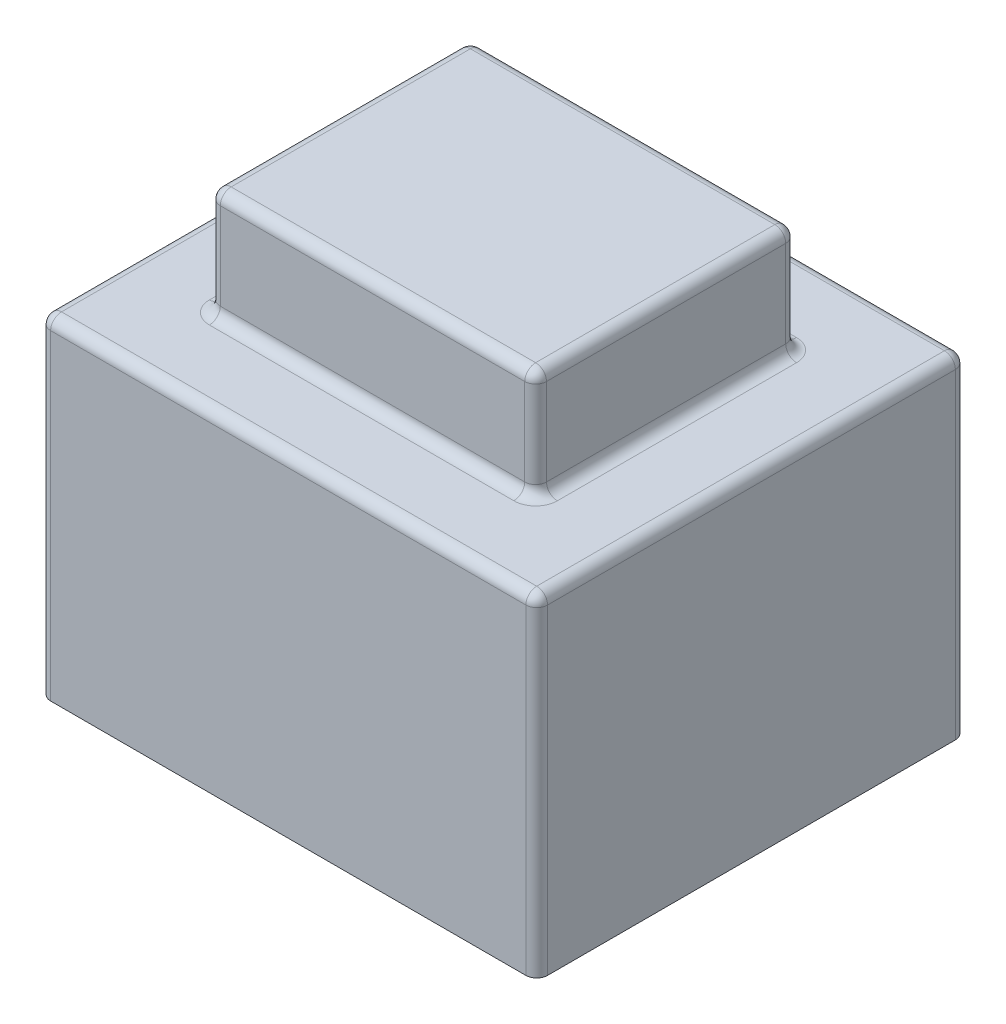
SolidWorks part; units mm, degrees
ref_plane "Спереди" through (0, 0, 0) normal (0, 0, 1) x (1, 0, 0)
ref_plane "Сверху" through (0, 0, 0) normal (0, 1, 0) x (1, 0, 0)
ref_plane "Справа" through (0, 0, 0) normal (1, 0, 0) x (0, 0, -1)
sketch "Эскиз1" plane through (0, 0, 0) normal (0, 1, 0) x (1, 0, 0)
  line L0 (-5.5, 13.5) -> (-5.5, 11.5)
  line L1 (-10.5, 13.5) -> (-9.5, 13.5)
  line L2 (-10.5, 13.5) -> (-10.5, 11.5)
  line L3 (-10.5, 11.5) -> (-9.5, 11.5)
  line L4 (-9.5, 13.5) -> (-9.5, 11.5)
  line L5 (-10.5, 13.5) -> (-9.5, 11.5) construction
  line L6 (-10.5, 11.5) -> (-9.5, 13.5) construction
  line L7 (-5.5, 13.5) -> (-4.5, 13.5)
  line L8 (-4.5, 13.5) -> (-4.5, 11.5)
  line L9 (-5.5, 11.5) -> (-4.5, 11.5)
  line L10 (-0.5, 13.5) -> (-0.5, 11.5)
  line L11 (-0.5, 13.5) -> (0.5, 13.5)
  line L12 (0.5, 13.5) -> (0.5, 11.5)
  line L13 (-0.5, 11.5) -> (0.5, 11.5)
  line L14 (4.5, 13.5) -> (4.5, 11.5)
  line L15 (4.5, 13.5) -> (5.5, 13.5)
  line L16 (5.5, 13.5) -> (5.5, 11.5)
  line L17 (4.5, 11.5) -> (5.5, 11.5)
  line L18 (9.5, 13.5) -> (9.5, 11.5)
  line L19 (9.5, 13.5) -> (10.5, 13.5)
  line L20 (10.5, 13.5) -> (10.5, 11.5)
  line L21 (9.5, 11.5) -> (10.5, 11.5)
  line L22 (-5.5, -11.5) -> (-5.5, -13.5)
  line L23 (-5.5, -11.5) -> (-4.5, -11.5)
  line L24 (-4.5, -11.5) -> (-4.5, -13.5)
  line L25 (-5.5, -13.5) -> (-4.5, -13.5)
  line L26 (-0.5, -11.5) -> (-0.5, -13.5)
  line L27 (-0.5, -11.5) -> (0.5, -11.5)
  line L28 (0.5, -11.5) -> (0.5, -13.5)
  line L29 (-0.5, -13.5) -> (0.5, -13.5)
  line L30 (4.5, -11.5) -> (4.5, -13.5)
  line L31 (4.5, -11.5) -> (5.5, -11.5)
  line L32 (5.5, -11.5) -> (5.5, -13.5)
  line L33 (4.5, -13.5) -> (5.5, -13.5)
  line L34 (9.5, -11.5) -> (9.5, -13.5)
  line L35 (9.5, -11.5) -> (10.5, -11.5)
  line L36 (10.5, -11.5) -> (10.5, -13.5)
  line L37 (9.5, -13.5) -> (10.5, -13.5)
  line L38 (-10.5, -11.5) -> (-10.5, -13.5)
  line L39 (-10.5, -11.5) -> (-9.5, -11.5)
  line L40 (-9.5, -11.5) -> (-9.5, -13.5)
  line L41 (-10.5, -13.5) -> (-9.5, -13.5)
  point P0 (-10, 12.5)
  dimension "D1" = 5
  dimension "D2" = 2
extrude "Бобышка-Вытянуть1" add sketch "Эскиз1" along normal blind 1.5 from offset 0.5 offset against normal yes
sketch "Эскиз2" plane through (0, 1, 0) normal (0, 1, 0) x (1, 0, 0)
  line L1 (-22.85, 19.75) -> (22.85, 19.75)
  line L2 (-22.85, 19.75) -> (-22.85, -19.75)
  line L3 (-22.85, -19.75) -> (22.85, -19.75)
  line L4 (22.85, 19.75) -> (22.85, -19.75)
  point P4 (0, 0)
  point P5 (0, 0)
  point P6 (0, 0)
  point P7 (0, 0)
  point P8 (0, 0)
  point P9 (0, 0)
extrude "Бобышка-Вытянуть2" add sketch "Эскиз2" along normal blind 30.5 separate body
sketch "Эскиз3" plane through (0, 31.5, 0) normal (0, 1, 0) x (1, 0, 0)
  line L1 (-15, 12) -> (15, 12)
  line L2 (-15, 12) -> (-15, -12)
  line L3 (-15, -12) -> (15, -12)
  line L4 (15, 12) -> (15, -12)
  point P4 (0, 0)
  point P6 (0, 0)
  point P7 (0, 0)
extrude "Бобышка-Вытянуть3" add sketch "Эскиз3" along normal blind 10
fillet "Скругление1" radius 1 20 edges at (-15, 36.5, -12) (15, 36.5, -12) (-15, 36.5, 12) (15, 36.5, 12) (0, 41.5, -12) (15, 41.5, 0) (0, 41.5, 12) (-15, 41.5, 0) (15, 31.5, 0) (0, 31.5, -12) (-15, 31.5, 0) (0, 31.5, 12) (0, 31.5, -19.75) (22.85, 31.5, 0) (0, 31.5, 19.75) (-22.85, 31.5, 0) (-22.85, 16.25, -19.75) (22.85, 16.25, -19.75) (-22.85, 16.25, 19.75) (22.85, 16.25, 19.75)
